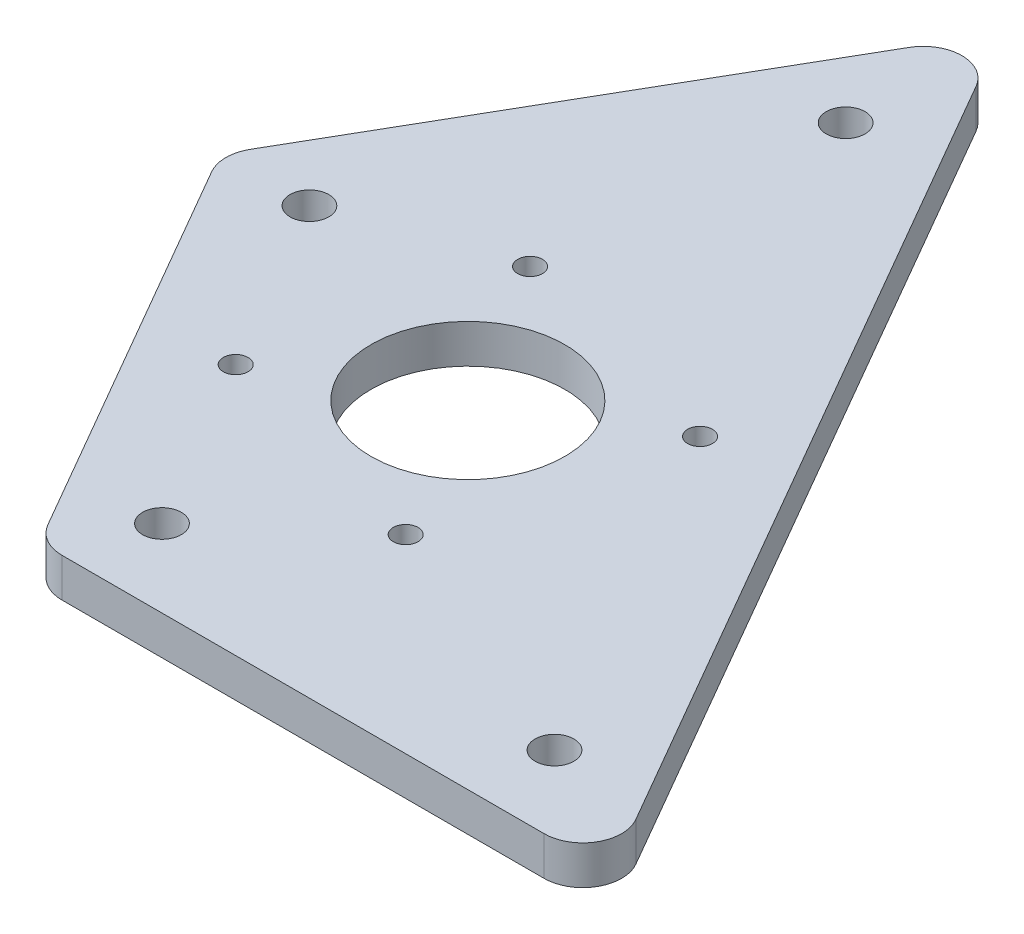
SolidWorks part; units mm, degrees
ref_plane "Alzado" through (0, 0, 0) normal (0, 0, 1) x (1, 0, 0)
ref_plane "Planta" through (0, 0, 0) normal (0, 1, 0) x (1, 0, 0)
ref_plane "Vista lateral" through (0, 0, 0) normal (1, 0, 0) x (0, 0, -1)
sketch "Croquis1" plane through (0, 0, 0) normal (0, 1, 0) x (1, 0, 0)
  line L0 (0, 0) -> (102.5843, 0) construction
  line L1 (0, 0) -> (51.2922, 88.8406) construction
  line L2 (38.9711, 22.5) -> (68.9148, 14.4766) construction
  line L3 (68.9148, 14.4766) -> (76.9382, 44.4203) construction
  line L4 (76.9382, 44.4203) -> (46.9945, 52.4437) construction
  line L5 (46.9945, 52.4437) -> (38.9711, 22.5) construction
  line L6 (76.9382, 44.4203) -> (38.9711, 22.5) construction
  line L7 (46.9945, 52.4437) -> (68.9148, 14.4766) construction
  line L8 (102.5843, 0) -> (51.2922, 88.8406) construction
  line L9 (25.9808, 45) -> (51.9615, 0) construction
  line L10 (17.3205, 10) -> (57.0657, 78.8406) construction
  line L11 (51.2922, 108.8406) -> (119.9048, -10)
  line L12 (119.9048, -10) -> (46.188, -10)
  line L13 (46.188, -10) -> (14.4338, 45)
  line L14 (14.4338, 45) -> (51.2922, 108.8406)
  line L15 (17.3205, 10) -> (96.8108, 10) construction
  line L16 (0, 10) -> (102.5843, 10) construction
  line L17 (8.6603, -5) -> (59.9524, 83.8406) construction
  circle A0 centre (51.2922, 88.8406) radius 2.5
  circle A1 centre (102.5843, 0) radius 2.5
  circle A2 centre (51.9615, 0) radius 2.5
  circle A3 centre (25.9808, 45) radius 2.5
  circle A4 centre (38.9711, 22.5) radius 1.6
  circle A5 centre (46.9945, 52.4437) radius 1.6
  circle A6 centre (76.9382, 44.4203) radius 1.6
  circle A7 centre (68.9148, 14.4766) radius 1.6
  circle A8 centre (57.9547, 33.4602) radius 12.5
  point P10 (0, 0)
  point P11 (0, 0)
  point P13 (76.9382, 44.4203)
  point P14 (38.9711, 22.5)
  point P32 (79.4903, 10)
  point P35 (48.4324, 63.7938)
  point P38 (17.3125, 10)
  point P39 (15.9463, 10)
  dimension "D3" = 5
  dimension "D11" = 25
  dimension "D12" = 3.2
  dimension "D1" = 60
  dimension "D2" = 31
  dimension "D5" = 10
  dimension "D6" = 45
  dimension "D7" = 10
  dimension "D8" = 10
  dimension "D9" = 10
  dimension "D10" = 10
  dimension "D4" = 10
extrude "Saliente-Extruir1" add sketch "Croquis1" along normal blind 5
fillet "Redondeo1" radius 5 4 edges at (14.4338, 2.5, -45) (51.2922, 2.5, -108.8406) (46.188, 2.5, 10) (119.9048, 2.5, 10)
